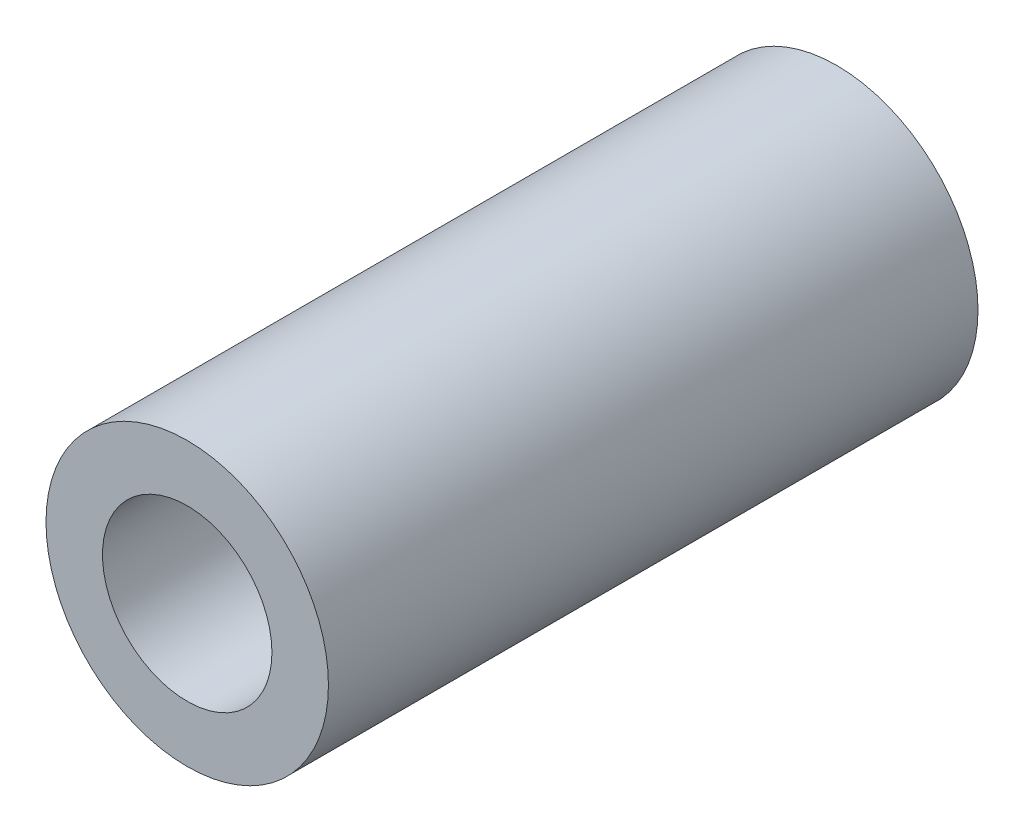
SolidWorks part; units mm, degrees
ref_plane "前视基准面" through (0, 0, 0) normal (0, 0, 1) x (1, 0, 0)
ref_plane "上视基准面" through (0, 0, 0) normal (0, 1, 0) x (1, 0, 0)
ref_plane "右视基准面" through (0, 0, 0) normal (1, 0, 0) x (0, 0, -1)
sketch "草图1" plane through (0, 0, 0) normal (0, 0, 1) x (1, 0, 0)
  circle A0 centre (0, 0) radius 3
  circle A1 centre (0, 0) radius 5
  dimension "D1" = 10
  dimension "D2" = 6
extrude "凸台-拉伸1" add sketch "草图1" along normal blind 23
